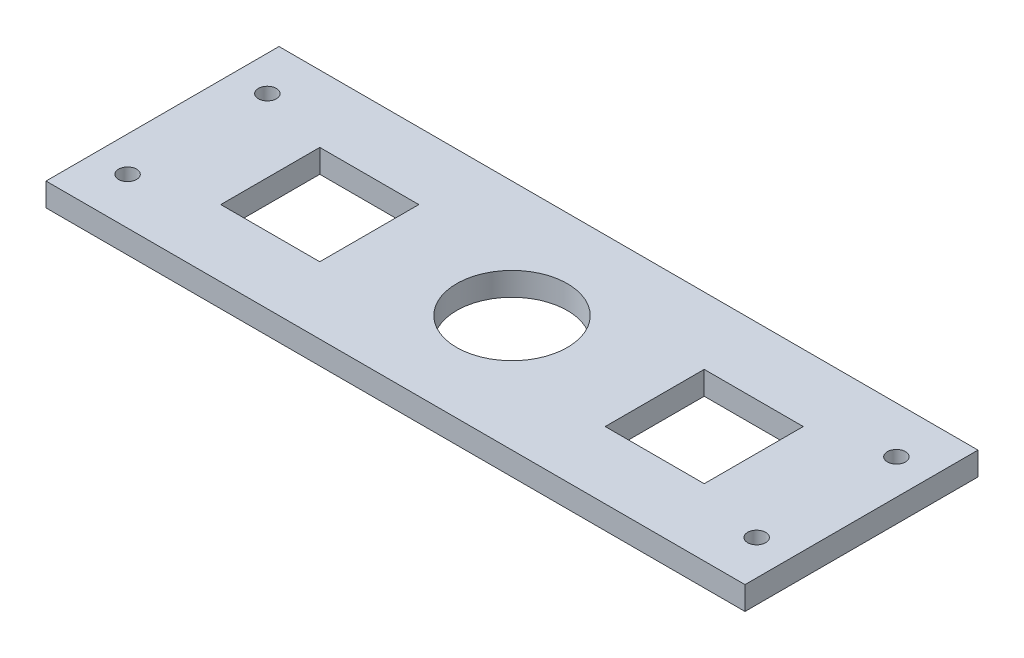
SolidWorks part; units mm, degrees
ref_plane "Front Plane" through (0, 0, 0) normal (0, 0, 1) x (1, 0, 0)
ref_plane "Top Plane" through (0, 0, 0) normal (0, 1, 0) x (1, 0, 0)
ref_plane "Right Plane" through (0, 0, 0) normal (1, 0, 0) x (0, 0, -1)
sketch "Sketch1" plane through (0, 0, 0) normal (0, 1, 0) x (1, 0, 0)
  line L1 (0, 0) -> (190.5, 0)
  line L2 (0, 0) -> (0, 63.5)
  line L3 (0, 63.5) -> (190.5, 63.5)
  line L4 (190.5, 0) -> (190.5, 63.5)
  dimension "D1" = 190.5
  dimension "D2" = 63.5
extrude "Boss-Extrude1" add sketch "Sketch1" along normal blind 6.35
sketch "Sketch3" plane through (0, 6.35, 0) normal (0, 1, 0) x (1, 0, 0)
  line L1 (29.3687, 45.2437) -> (56.3562, 45.2437)
  line L2 (29.3687, 45.2437) -> (29.3687, 18.2562)
  line L3 (29.3687, 18.2562) -> (56.3562, 18.2563)
  line L4 (56.3562, 45.2437) -> (56.3562, 18.2563)
  line L5 (0, 0) -> (190.5, 0) construction
  line L6 (0, 63.5) -> (0, 0) construction
  point P4 (56.3562, 31.75)
  dimension "D1" = 26.9875
  dimension "D2" = 26.9875
  dimension "D3" = 31.75
  dimension "D4" = 29.3687
extrude "Cut-Extrude2" cut sketch "Sketch3" against normal through all
sketch "Sketch4" plane through (0, 6.35, 0) normal (0, 1, 0) x (1, 0, 0)
  line L0 (0, 0) -> (190.5, 0) construction
  line L1 (134.1438, 45.2437) -> (161.1312, 45.2437)
  line L2 (134.1438, 45.2437) -> (134.1438, 18.2562)
  line L3 (134.1438, 18.2562) -> (161.1312, 18.2563)
  line L4 (161.1312, 45.2437) -> (161.1312, 18.2563)
  line L7 (190.5, 0) -> (190.5, 63.5) construction
  point P4 (161.1312, 31.75)
  dimension "D1" = 26.9875
  dimension "D2" = 26.9875
  dimension "D3" = 31.75
  dimension "D4" = 29.3687
extrude "Cut-Extrude3" cut sketch "Sketch4" against normal through all
sketch "Sketch5" plane through (0, 6.35, 0) normal (0, 1, 0) x (1, 0, 0)
  line L0 (190.5, 63.5) -> (0, 63.5) construction
  circle A0 centre (95.25, 31.75) radius 15.0812
  dimension "D1" = 30.1625
  dimension "D2" = 31.75
extrude "Cut-Extrude4" cut sketch "Sketch5" against normal through all
hole_wizard "#10 (0.1935) Diameter Hole1" positions "Sketch6" profile "Sketch7" hole size "#10" standard "ANSI Inch" end condition through all
sketch "Sketch6" plane through (0, 6.35, 0) normal (0, 1, 0) x (1, 0, 0)
  line L0 (190.5, 63.5) -> (0, 63.5) construction
  line L1 (0, 63.5) -> (0, 0) construction
  line L2 (0, 0) -> (190.5, 0) construction
  line L3 (190.5, 0) -> (190.5, 63.5) construction
  point P0 (9.525, 50.8)
  point P2 (9.525, 12.7)
  point P4 (180.975, 12.7)
  point P6 (180.975, 50.8)
  dimension "D1" = 12.7
  dimension "D2" = 9.525
  dimension "D3" = 9.525
  dimension "D4" = 12.7
  dimension "D5" = 9.525
  dimension "D6" = 9.525
  dimension "D7" = 12.7
  dimension "D8" = 12.7
sketch "Sketch7" plane through (9.525, 6.35, -50.8) normal (1, 0, 0) x (0, 0, 1)
  line L0 (0, 0) -> (0, 6.35)
  line L1 (0, 6.35) -> (2.4574, 6.35)
  line L2 (2.4574, 6.35) -> (2.4574, 0)
  line L5 (2.4574, 0) -> (0, 0)
  line L11 (0, -6.35) -> (0, 107.95) construction
  dimension "Thru Hole Dia." = 4.9149
  dimension "Thru Hole Depth" = 6.35
